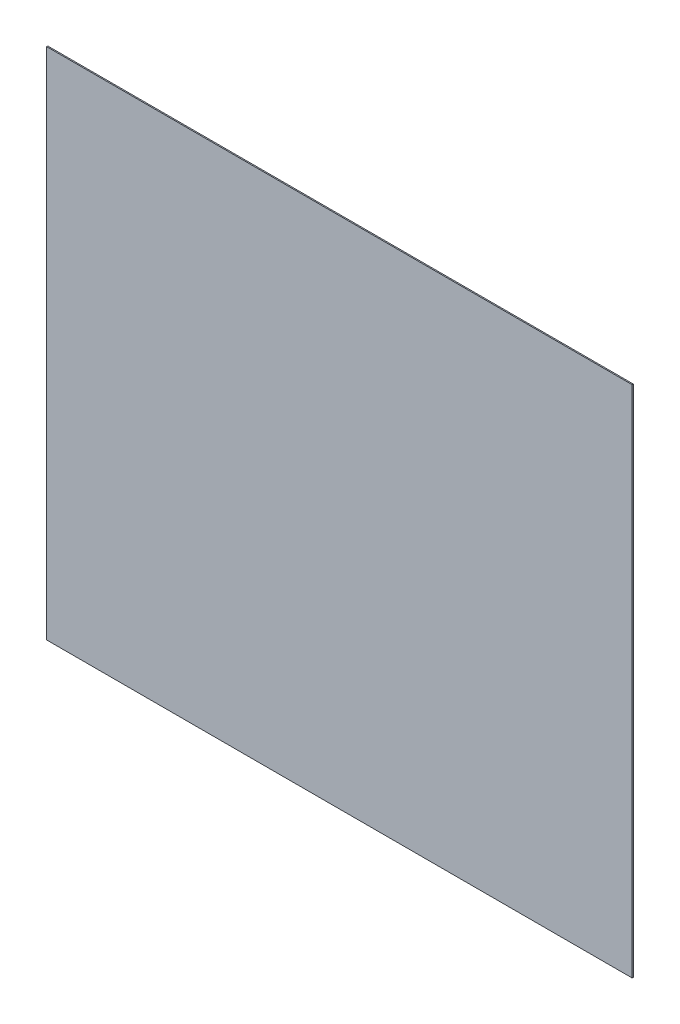
SolidWorks part; units mm, degrees
ref_plane "Alzado" through (0, 0, 0) normal (0, 0, 1) x (1, 0, 0)
ref_plane "Planta" through (0, 0, 0) normal (0, 1, 0) x (1, 0, 0)
ref_plane "Vista lateral" through (0, 0, 0) normal (1, 0, 0) x (0, 0, -1)
sketch "Croquis1" plane through (0, 0, 0) normal (0, 0, 1) x (1, 0, 0)
  line L1 (0, 0) -> (1481.2, 0)
  line L2 (0, 0) -> (0, -1300)
  line L3 (0, -1300) -> (1481.2, -1300)
  line L4 (1481.2, 0) -> (1481.2, -1300)
  dimension "D1" = 1481.2
  dimension "D2" = 1300
extrude "Saliente-Extruir1" add sketch "Croquis1" along normal blind 2.9
